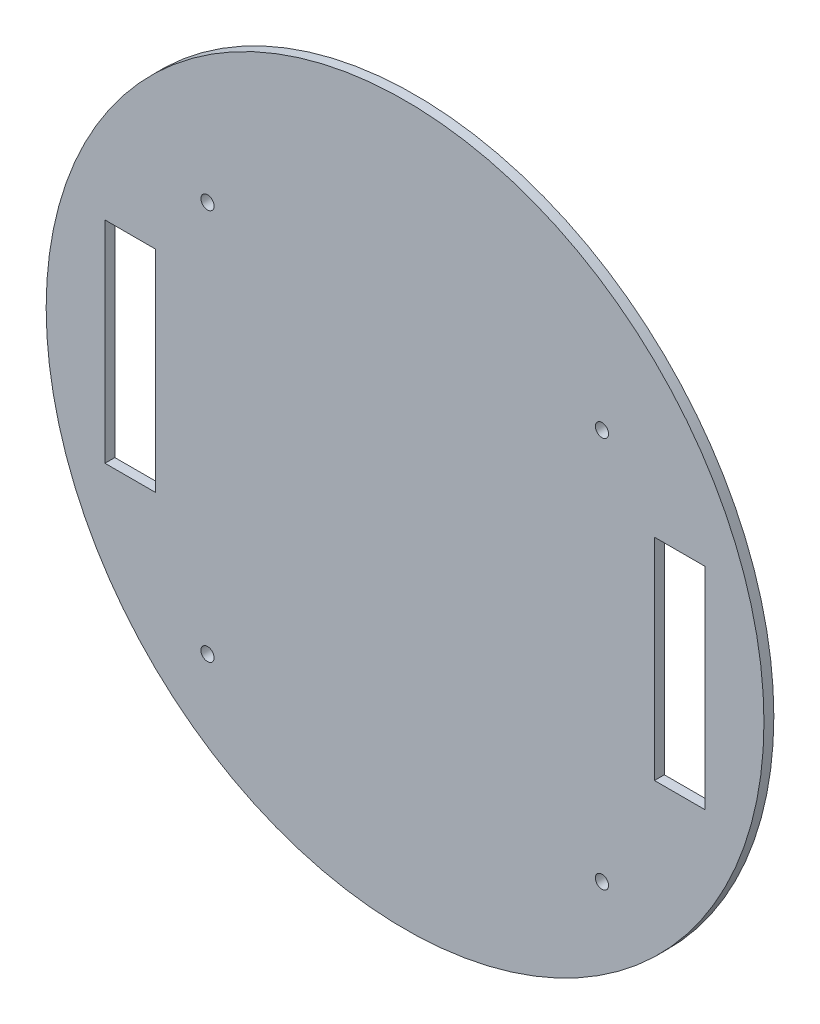
SolidWorks part; units mm, degrees
ref_plane "Front Plane" through (0, 0, 0) normal (0, 0, 1) x (1, 0, 0)
ref_plane "Top Plane" through (0, 0, 0) normal (0, 1, 0) x (1, 0, 0)
ref_plane "Right Plane" through (0, 0, 0) normal (1, 0, 0) x (0, 0, -1)
sketch "Sketch1" plane through (0, 0, 0) normal (0, 0, 1) x (1, 0, 0)
  line L0 (0, 49.9764) -> (0, -48.0665) construction
  line L17 (-50.2174, 54.11) -> (-45.4683, 54.11) construction
  circle A0 centre (0, 0) radius 54.5
  point P9 (-41.706, 54.11)
  point P18 (41.706, 54.11)
  dimension "D1" = 109
  dimension "D7" = 83.412
extrude "Boss-Extrude1" add sketch "Sketch1" along normal blind 1.5
sketch "Sketch2" plane through (0, 0, 1.5) normal (0, 0, 1) x (1, 0, 0)
  line L0 (-0.0496, 45.441) -> (-0.0496, -29.5416) construction
  line L1 (29.9004, -33.3) -> (-29.9996, -33.3) construction
  line L2 (29.9004, -33.3) -> (29.9004, 26.1) construction
  line L3 (29.9004, 26.1) -> (-29.9996, 26.1) construction
  line L4 (-29.9996, -33.3) -> (-29.9996, 26.1) construction
  line L5 (29.9004, -33.3) -> (-29.9996, 26.1) construction
  line L6 (29.9004, 26.1) -> (-29.9996, -33.3) construction
  circle A0 centre (29.9004, 26.1) radius 1
  circle A1 centre (29.9004, -33.3) radius 1
  circle A2 centre (-29.9996, -33.3) radius 1
  circle A3 centre (-29.9996, 26.1) radius 1
  point P0 (-0.0846, 4.3448)
  dimension "D1" = 2
  dimension "D2" = 61.4
  dimension "D3" = 61.9
extrude "Cut-Extrude1" cut sketch "Sketch2" against normal blind 1.58
sketch "Skica1" plane through (0, 0, 1.5) normal (0, 0, 1) x (1, 0, 0)
  line L0 (54.5, 0) -> (-54.5, 0) construction
  line L1 (45.5705, -16) -> (37.8705, -16)
  line L2 (45.5705, -16) -> (45.5705, 16)
  line L3 (45.5705, 16) -> (37.8705, 16)
  line L4 (37.8705, -16) -> (37.8705, 16)
  line L5 (0, -54.5) -> (0, 54.5) construction
  line L6 (-45.5705, 16) -> (-37.8705, 16)
  line L7 (-37.8705, -16) -> (-37.8705, 16)
  line L8 (-45.5705, -16) -> (-45.5705, 16)
  line L9 (-45.5705, -16) -> (-37.8705, -16)
  line L10 (41.7205, -16) -> (41.7205, 16) construction
  circle A0 centre (0, 0) radius 54.5 construction
  dimension "D1" = 16.6295
  dimension "D2" = 7.7
  dimension "D3" = 32
extrude "Odebrat vysunutím1" cut sketch "Skica1" against normal up to surface (1.5 mm away) up to face at (-28.9996, 26.1, 0)
